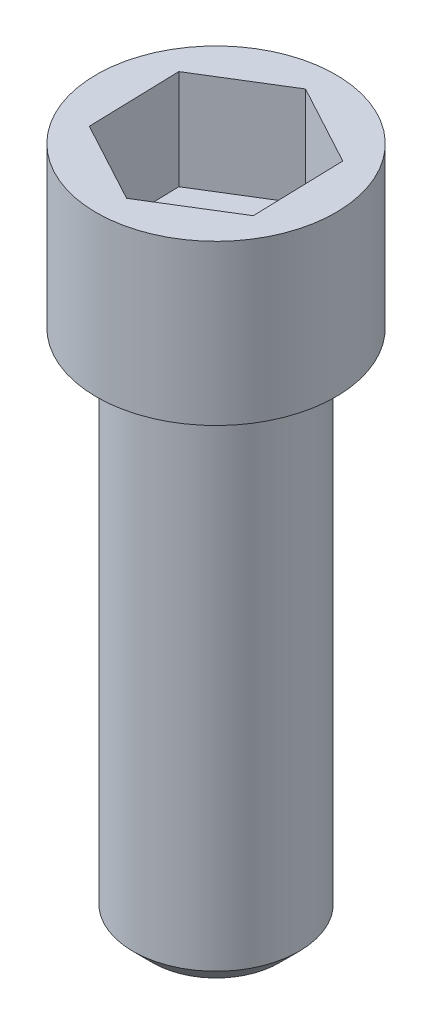
SolidWorks part; units mm, degrees
material "Plain Carbon Steel"
ref_plane "Front" through (0, 0, 0) normal (0, 0, 1) x (1, 0, 0)
ref_plane "Top" through (0, 0, 0) normal (0, 1, 0) x (1, 0, 0)
ref_plane "Right" through (0, 0, 0) normal (1, 0, 0) x (0, 0, -1)
sketch "Sketch1" plane through (0, 0, 0) normal (0, 1, 0) x (1, 0, 0)
  circle A0 centre (0, 0) radius 1.04
  dimension "D1" = 2.08
extrude "Boss-Extrude1" add sketch "Sketch1" along normal blind 6.5
sketch "Sketch2" plane through (0, 6.5, 0) normal (0, 1, 0) x (1, 0, 0)
  circle A0 centre (0, 0) radius 1.5
  dimension "D1" = 3
extrude "Boss-Extrude2" add sketch "Sketch2" along normal blind 2
sketch "Sketch3" plane through (0, 8.5, 0) normal (0, 1, 0) x (1, 0, 0)
  line L1 (-0.0328, 1.1542) -> (-1.016, 0.5487)
  line L2 (-1.016, 0.5487) -> (-0.9832, -0.6055)
  line L3 (-0.9832, -0.6055) -> (0.0328, -1.1542)
  line L4 (0.0328, -1.1542) -> (1.016, -0.5487)
  line L5 (1.016, -0.5487) -> (0.9832, 0.6055)
  line L6 (0.9832, 0.6055) -> (-0.0328, 1.1542)
  circle A0 centre (0, 0) radius 1 construction
  dimension "D1" = 2
  dimension "D2" = 0.9832
extrude "Cut-Extrude1" cut sketch "Sketch3" against normal blind 1.25
chamfer "Chamfer1" distance 0.25 angle 45 1 edges at (0, 0, 1.04)
